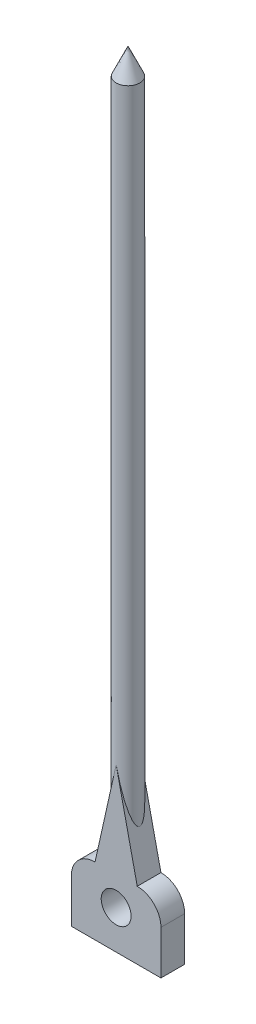
SolidWorks part; units mm, degrees
ref_plane "Front Plane" through (0, 0, 0) normal (0, 0, 1) x (1, 0, 0)
ref_plane "Top Plane" through (0, 0, 0) normal (0, 1, 0) x (1, 0, 0)
ref_plane "Right Plane" through (0, 0, 0) normal (1, 0, 0) x (0, 0, -1)
sketch "Sketch3" plane through (0, 0, 0) normal (0, 0, 1) x (1, 0, 0)
  line L0 (4.4483, 6.1) -> (-4.4483, 6.1)
  line L1 (-9.4483, 1.1) -> (-9.4483, -10.15)
  line L2 (-9.4483, -10.15) -> (9.4483, -10.15)
  line L3 (9.4483, -10.15) -> (9.4483, 1.1)
  line L4 (-9.4483, -8.15) -> (9.4483, -8.15)
  circle A0 centre (0, 0) radius 3.15
  arc A1 (-4.4483, 6.1) -> (-9.4483, 1.1) centre (-4.4483, 1.1) ccw
  arc A2 (9.4483, 1.1) -> (4.4483, 6.1) centre (4.4483, 1.1) ccw
  dimension "D1" = 6.3
  dimension "D2" = 2
extrude "Boss-Extrude1" add sketch "Sketch3" along normal blind 5 contours L3 A2 L0 A1 L1 L4 A0
sketch "Sketch4" plane through (0, 6.1, 0) normal (0, 1, 0) x (1, 0, 0)
  line L1 (4.4483, 0) -> (-4.4483, 0) construction
  circle A0 centre (0, -2.5) radius 2.5
  dimension "D2" = 5
  dimension "D1" = 2.5
extrude "Boss-Extrude2" add sketch "Sketch4" along normal blind 150
sketch "Sketch6" plane through (0, 0, 0) normal (1, 0, 0) x (0, 0, -1)
  line L0 (-2.5, 156.1) -> (0, 150.6029)
  line L1 (0, 156.1) -> (-5, 156.1) construction
  line L2 (0, 6.1) -> (0, 156.1) construction
  line L5 (-2.5, 156.1) -> (-2.5, 160.4362)
  line L6 (-2.5, 157.4755) -> (2.0647, 157.4755)
  line L7 (2.0647, 157.4755) -> (0, 150.6029)
revolve "Cut-Revolve2" cut sketch "Sketch6" angle 360 about L5
sketch "Sketch7" plane through (0, 0, 0) normal (0, 0, -1) x (-1, 0, 0)
  line L0 (0, 26.0765) -> (4.4483, 6.1)
  line L1 (0, 26.0765) -> (-4.4483, 6.1)
  line L2 (-4.4483, 6.1) -> (4.4483, 6.1)
  arc A0 (9.4483, 1.1) -> (4.4483, 6.1) centre (4.4483, 1.1) ccw construction
  arc A1 (-4.4483, 6.1) -> (-9.4483, 1.1) centre (-4.4483, 1.1) ccw construction
extrude "Boss-Extrude3" add sketch "Sketch7" against normal up to surface (5 mm away) up to face at (3.15, 0, 5)
